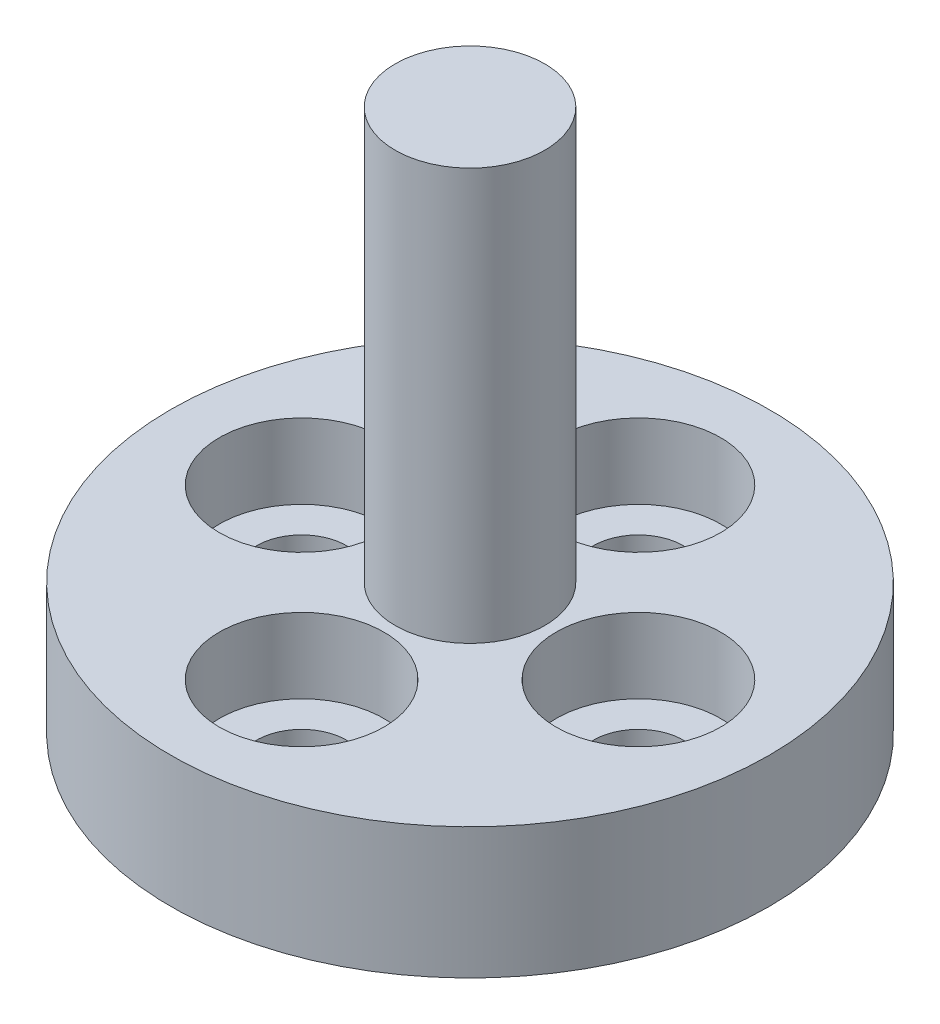
SolidWorks part; units mm, degrees
ref_plane "前视基准面" through (0, 0, 0) normal (0, 0, 1) x (1, 0, 0)
ref_plane "上视基准面" through (0, 0, 0) normal (0, 1, 0) x (1, 0, 0)
ref_plane "右视基准面" through (0, 0, 0) normal (1, 0, 0) x (0, 0, -1)
sketch "草图1" plane through (0, 0, 0) normal (0, 0, 1) x (1, 0, 0)
  line L0 (0, 0) -> (8, 0)
  line L1 (8, 0) -> (8, 3.5)
  line L2 (8, 3.5) -> (2, 3.5)
  line L3 (2, 3.5) -> (2, 14.5)
  line L4 (2, 14.5) -> (0, 14.5)
  line L5 (0, 14.5) -> (0, 0)
  dimension "D1" = 8
  dimension "D2" = 14.5
  dimension "D3" = 11
  dimension "D4" = 2
revolve "旋转1" add sketch "草图1" angle 360 about L5
sketch "草图2" plane through (0, 3.5, 0) normal (0, 1, 0) x (1, 0, 0)
  circle A0 centre (0, 0) radius 4.5
  dimension "D1" = 9
hole_wizard "M2 凹头盖螺钉的柱形沉头孔1" positions "草图9" profile "草图10" counterbore size "M2" standard "ANSI Metric" end condition through all
sketch "草图9" plane through (0, 3.5, 0) normal (0, 1, 0) x (1, 0, 0)
  circle A0 centre (0, 0) radius 4.5 construction
  point P0 (-4.5, 0)
  point P4 (0, 4.5)
  point P6 (4.5, 0)
  point P8 (0, -4.5)
sketch "草图10" plane through (-4.5, 3.5, 0) normal (1, 0, 0) x (0, 0, 1)
  line L0 (0, 0) -> (0, 3.5)
  line L1 (0, 3.5) -> (1.2, 3.5)
  line L3 (1.2, 3.5) -> (1.2, 2)
  line L4 (1.2, 2) -> (2.2, 2)
  line L5 (2.2, 2) -> (2.2, 0)
  line L7 (2.2, 0) -> (0, 0)
  line L11 (0, -6.35) -> (0, 107.95) construction
  dimension "通孔孔直径" = 2.4
  dimension "通孔孔深度" = 3.5
  dimension "柱形沉头孔直径" = 4.4
  dimension "柱形沉头孔深度" = 2
